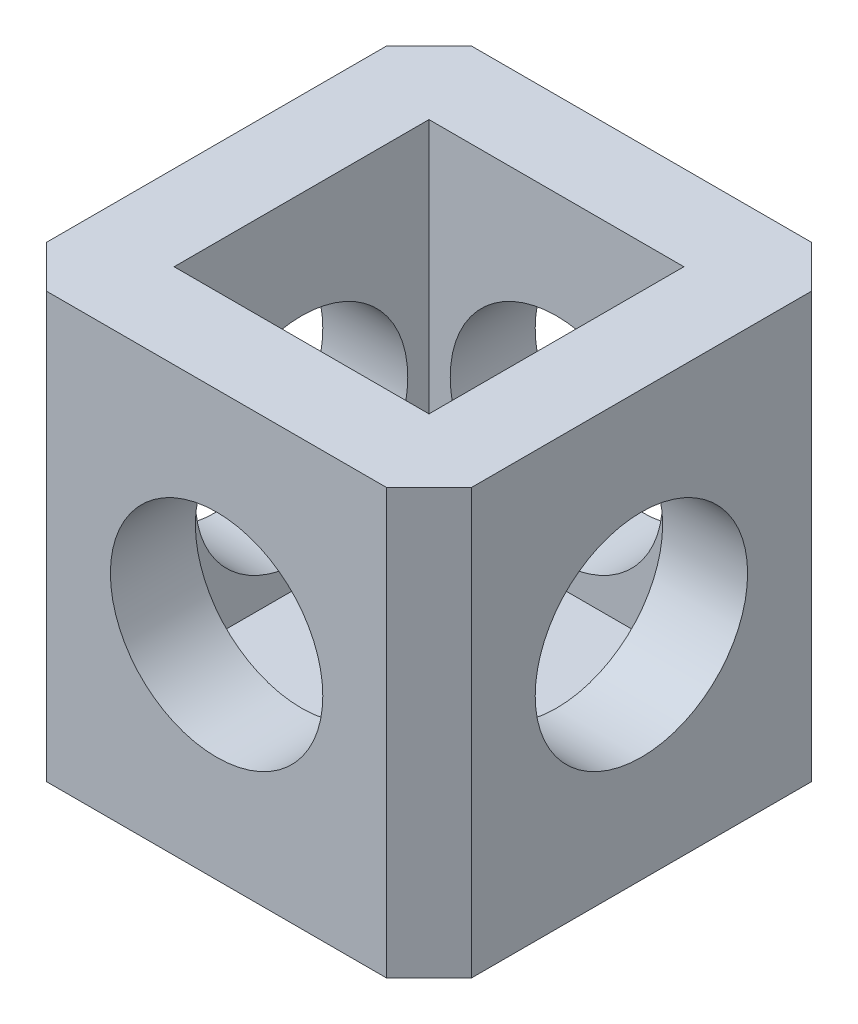
SolidWorks part; units mm, degrees
ref_plane "Plan de face" through (0, 0, 0) normal (0, 0, 1) x (1, 0, 0)
ref_plane "Plan de dessus" through (0, 0, 0) normal (0, 1, 0) x (1, 0, 0)
ref_plane "Plan de droite" through (0, 0, 0) normal (1, 0, 0) x (0, 0, -1)
sketch "Esquisse1" plane through (0, 0, 0) normal (0, 1, 0) x (1, 0, 0)
  line L0 (-10, -10) -> (-10, 10)
  line L1 (-55, 0) -> (55, 0) construction
  line L2 (-10, 10) -> (10, 10)
  line L3 (0, -55) -> (0, 55) construction
  line L4 (10, -10) -> (10, 10)
  line L5 (-10, -10) -> (10, -10)
  point P0 (0, -10)
  point P8 (0, 10)
  point P10 (10, 0)
  point P11 (-10, 0)
  dimension "D1" = 10
  dimension "D2" = 10
extrude "Boss.-Extru.1" add sketch "Esquisse1" along normal blind 4
sketch "Esquisse4" plane through (0, 4, 0) normal (0, 1, 0) x (1, 0, 0)
  line L1 (-10, 10) -> (10, 10)
  line L2 (-10, 10) -> (-10, -10)
  line L3 (-10, -10) -> (10, -10)
  line L4 (10, 10) -> (10, -10)
  line L5 (-6, 6) -> (6, 6)
  line L6 (-6, 6) -> (-6, -6)
  line L7 (-6, -6) -> (6, -6)
  line L8 (6, 6) -> (6, -6)
  dimension "D1" = 4
  dimension "D2" = 12
  dimension "D3" = 12
  dimension "D4" = 4
extrude "Boss.-Extru.2" add sketch "Esquisse4" along normal blind 16
sketch "Esquisse5" plane through (0, 0, 10) normal (0, 0, 1) x (1, 0, 0)
  line L4 (0, -11) -> (0, 11) construction
  line L5 (11, 0) -> (-11, 0) construction
  circle A0 centre (0, 10) radius 5
  dimension "D2" = 10
  dimension "D1" = 10
sketch "Esquisse6" plane through (10, 0, 0) normal (1, 0, 0) x (0, 0, -1)
  line L3 (0, 11) -> (0, -11) construction
  line L4 (11, 0) -> (-11, 0) construction
  circle A0 centre (0, 10) radius 5
  dimension "D1" = 10
extrude "Enlèv. mat.-Extru.3" cut sketch "Esquisse6" against normal blind 25
extrude "Enlèv. mat.-Extru.4" cut sketch "Esquisse5" against normal blind 25
chamfer "Chanfrein1" distance 2 angle 45 4 edges at (-10, 10, 10) (10, 10, 10) (10, 10, -10) (-10, 10, -10)
